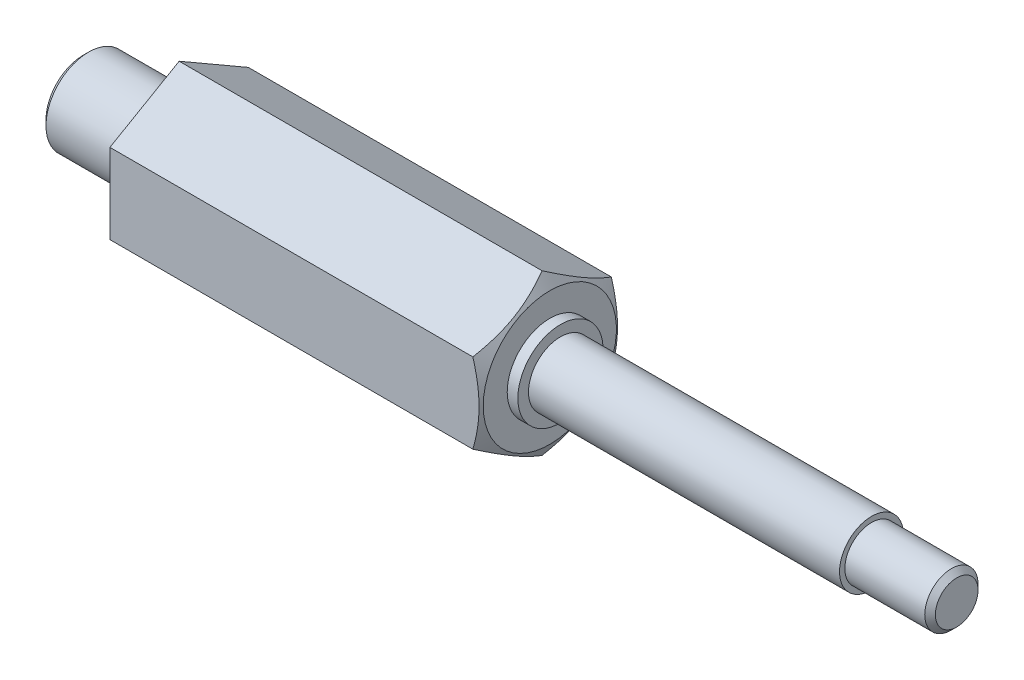
SolidWorks part; units mm, degrees
ref_plane "Front" through (0, 0, 0) normal (0, 0, 1) x (1, 0, 0)
ref_plane "Top" through (0, 0, 0) normal (0, 1, 0) x (1, 0, 0)
ref_plane "Right" through (0, 0, 0) normal (1, 0, 0) x (0, 0, -1)
sketch "Sketch1" plane through (0, 0, 0) normal (1, 0, 0) x (0, 0, -1)
  line L1 (0, 7.5056) -> (-6.5, 3.7528)
  line L2 (-6.5, 3.7528) -> (-6.5, -3.7528)
  line L3 (-6.5, -3.7528) -> (0, -7.5056)
  line L4 (0, -7.5056) -> (6.5, -3.7528)
  line L5 (6.5, -3.7528) -> (6.5, 3.7528)
  line L6 (6.5, 3.7528) -> (0, 7.5056)
  circle A0 centre (0, 0) radius 6.5 construction
  dimension "D1" = 13
extrude "Boss-Extrude1" add sketch "Sketch1" along normal blind 82 from offset 9 offset against normal yes
sketch "Sketch2" plane through (0, 0, 0) normal (0, 0, 1) x (1, 0, 0)
  line L0 (-20.132, 0) -> (84.4684, 0) construction
  line L1 (0, 7.5056) -> (-9, 7.5056)
  line L2 (73, 7.5056) -> (-9, 7.5056) construction
  line L3 (-9, 7.5056) -> (-9, 4)
  line L4 (-9, 3.7528) -> (-9, -3.7528) construction
  line L5 (-9, 4) -> (-1, 4)
  line L6 (-1, 4) -> (-1, 3.45)
  line L7 (-1, 3.45) -> (0, 3.45)
  line L8 (0, 3.45) -> (0, 7.5056)
  dimension "D1" = 8
  dimension "D2" = 6.9
  dimension "D3" = 1
revolve "Cut-Revolve1" cut sketch "Sketch2" angle 360 about L0
cosmetic thread "Cosmetic Thread1" parameters "D2"=6.619
sketch "Sketch3" plane through (0, 0, 0) normal (0, 0, 1) x (1, 0, 0)
  line L0 (-14.2462, 0) -> (77.0036, 0) construction
  line L1 (34.8, 7.5056) -> (34.8, 4)
  line L2 (73, 7.5056) -> (0, 7.5056) construction
  line L3 (34.8, 4) -> (35.8, 4)
  line L4 (35.8, 4) -> (35.8, 3)
  line L5 (35.8, 3) -> (65, 3)
  line L6 (65, 3) -> (65, 2.5)
  line L7 (65, 2.5) -> (73, 2.5)
  line L8 (73, 3.7528) -> (73, -3.7528) construction
  line L9 (73, 2.5) -> (73, 7.5056)
  line L10 (73, 7.5056) -> (34.8, 7.5056)
  line L11 (0, 3.7528) -> (0, 7.5056) construction
  dimension "D1" = 34.8
  dimension "D2" = 35.8
  dimension "D3" = 65
  dimension "D4" = 8
  dimension "D5" = 6
  dimension "D6" = 5
revolve "Cut-Revolve2" cut sketch "Sketch3" angle 360 about L0
cosmetic thread "Cosmetic Thread2" parameters "D1"=7, "D2"=4.11
sketch "Sketch4" plane through (0, 0, 0) normal (0, 0, 1) x (1, 0, 0)
  line L0 (34.8, 7.5056) -> (34.0751, 7.5056)
  line L1 (34.8, 7.5056) -> (0, 7.5056) construction
  line L2 (34.0751, 7.5056) -> (34.8, 6.25)
  line L3 (34.8, 7.5056) -> (34.8, 3.7528) construction
  line L4 (34.8, 6.25) -> (34.8, 7.5056)
  line L5 (-12.9362, 0) -> (76.062, 0) construction
  dimension "D1" = 12.5
  dimension "D2" = 30
revolve "Cut-Revolve3" cut sketch "Sketch4" angle 360 about L5
chamfer "Chamfer1" distance 0.5 2 edges at (73, 0, 2.5) (-9, 0, 4)
